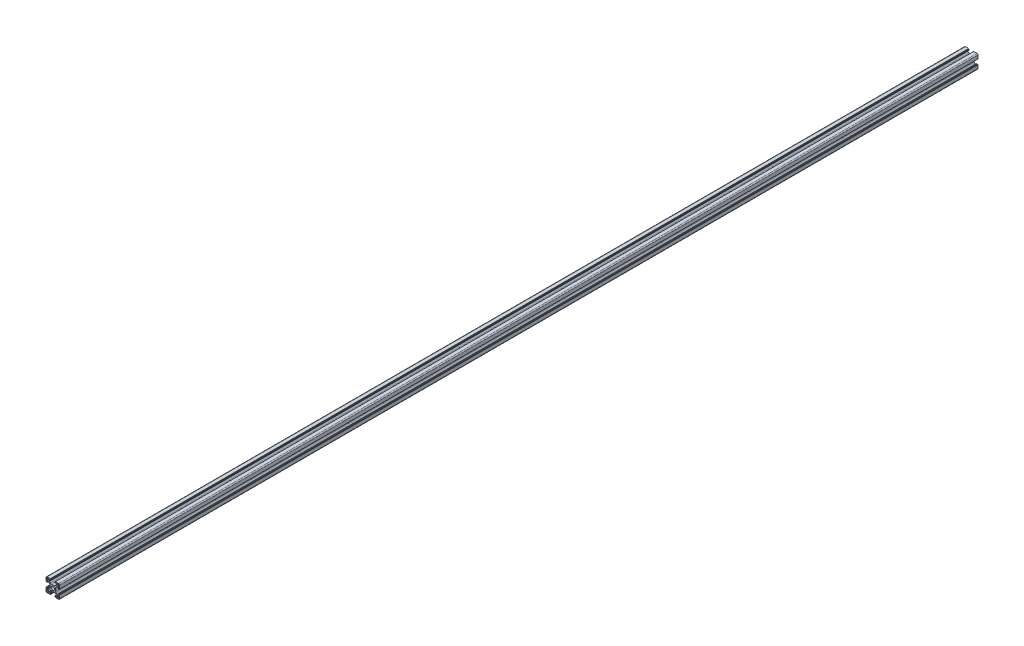
SolidWorks part; units mm, degrees
material "1060 Сплав"
ref_plane "Спереди" through (0, 0, 0) normal (0, 0, 1) x (1, 0, 0)
ref_plane "Сверху" through (0, 0, 0) normal (0, 1, 0) x (1, 0, 0)
ref_plane "Справа" through (0, 0, 0) normal (1, 0, 0) x (0, 0, -1)
sketch "Эскиз1" plane through (0, 0, 0) normal (0, 0, 1) x (1, 0, 0)
  line L0 (9.3595, 9.1357) -> (6.3595, 6.1357) construction
  line L1 (0.2595, 4.0357) -> (2.1582, 4.0357)
  line L2 (0.2595, 0.0357) -> (10.2595, 10.0357) construction
  line L3 (7.8595, 7.6357) -> (6.3595, 9.1357) construction
  line L4 (3.5725, 4.6215) -> (4.8737, 5.9227)
  line L5 (7.1595, 6.1357) -> (8.5595, 6.1357)
  line L6 (6.3595, 6.9357) -> (6.3595, 8.3357)
  line L7 (8.5595, 9.1357) -> (7.1595, 9.1357)
  line L8 (5.4595, 8.2357) -> (5.4595, 7.3369)
  line L9 (4.0227, 8.1089) -> (4.503, 8.5893)
  line L10 (3.4595, 9.5848) -> (3.9595, 9.5848)
  line L11 (3.8459, 8.0357) -> (3.5595, 8.0357)
  line L12 (4.8566, 8.7357) -> (4.9595, 8.7357)
  line L13 (3.9595, 9.8857) -> (3.9595, 9.5848)
  line L14 (3.3095, 9.4348) -> (3.3095, 8.2857)
  line L15 (8.7595, 10.0357) -> (4.1095, 10.0357)
  line L16 (9.3595, 8.3357) -> (9.3595, 6.9357)
  line L17 (10.2595, 8.5357) -> (10.2595, 3.8857)
  line L18 (9.6585, 3.0857) -> (8.5095, 3.0857)
  line L19 (10.1095, 3.7357) -> (9.8085, 3.7357)
  line L20 (8.9595, 4.6328) -> (8.9595, 4.7357)
  line L21 (8.2595, 3.6221) -> (8.2595, 3.3357)
  line L22 (9.8085, 3.2357) -> (9.8085, 3.7357)
  line L23 (8.3327, 3.7989) -> (8.813, 4.2793)
  line L24 (8.4595, 5.2357) -> (7.5607, 5.2357)
  line L25 (4.8452, 3.3487) -> (6.1465, 4.6499)
  line L26 (4.2595, 0.0357) -> (4.2595, 1.9345)
  line L27 (4.2595, 0.0357) -> (4.2595, -1.8631)
  line L28 (4.8452, -3.2773) -> (6.1465, -4.5785)
  line L29 (6.3595, -6.8643) -> (6.3595, -8.2643)
  line L30 (7.1595, -6.0643) -> (8.5595, -6.0643)
  line L31 (9.3595, -8.2643) -> (9.3595, -6.8643)
  line L32 (8.4595, -5.1643) -> (7.5607, -5.1643)
  line L33 (8.3327, -3.7275) -> (8.813, -4.2079)
  line L34 (9.8085, -3.1643) -> (9.8085, -3.6643)
  line L35 (8.2595, -3.5507) -> (8.2595, -3.2643)
  line L36 (8.9595, -4.5614) -> (8.9595, -4.6643)
  line L37 (10.1095, -3.6643) -> (9.8085, -3.6643)
  line L38 (9.6585, -3.0143) -> (8.5095, -3.0143)
  line L39 (10.2595, -8.4643) -> (10.2595, -3.8143)
  line L40 (8.5595, -9.0643) -> (7.1595, -9.0643)
  line L41 (8.7595, -9.9643) -> (4.1095, -9.9643)
  line L42 (3.3095, -9.3634) -> (3.3095, -8.2143)
  line L43 (3.9595, -9.8143) -> (3.9595, -9.5134)
  line L44 (4.8566, -8.6643) -> (4.9595, -8.6643)
  line L45 (3.8459, -7.9643) -> (3.5595, -7.9643)
  line L46 (3.4595, -9.5134) -> (3.9595, -9.5134)
  line L47 (4.0227, -8.0375) -> (4.503, -8.5179)
  line L48 (5.4595, -8.1643) -> (5.4595, -7.2655)
  line L49 (3.5725, -4.5501) -> (4.8737, -5.8513)
  line L50 (0.2595, -3.9643) -> (2.1582, -3.9643)
  line L51 (9.3595, -9.0643) -> (6.3595, -6.0643) construction
  line L52 (0.2595, 0.0357) -> (10.2595, -9.9643) construction
  line L53 (7.8595, -7.5643) -> (9.3595, -6.0643) construction
  line L54 (0.2595, -3.9643) -> (-1.6393, -3.9643)
  line L55 (-3.0535, -4.5501) -> (-4.3548, -5.8513)
  line L56 (-6.6405, -6.0643) -> (-8.0405, -6.0643)
  line L57 (-5.8405, -6.8643) -> (-5.8405, -8.2643)
  line L58 (-8.0405, -9.0643) -> (-6.6405, -9.0643)
  line L59 (-4.9405, -8.1643) -> (-4.9405, -7.2655)
  line L60 (-3.5038, -8.0375) -> (-3.9841, -8.5179)
  line L61 (-2.9405, -9.5134) -> (-3.4405, -9.5134)
  line L62 (-3.327, -7.9643) -> (-3.0405, -7.9643)
  line L63 (-4.3376, -8.6643) -> (-4.4405, -8.6643)
  line L64 (-3.4405, -9.8143) -> (-3.4405, -9.5134)
  line L65 (-2.7905, -9.3634) -> (-2.7905, -8.2143)
  line L66 (-8.2405, -9.9643) -> (-3.5905, -9.9643)
  line L67 (-8.8405, -8.2643) -> (-8.8405, -6.8643)
  line L68 (-9.7405, -8.4643) -> (-9.7405, -3.8143)
  line L69 (-9.1396, -3.0143) -> (-7.9905, -3.0143)
  line L70 (-9.5905, -3.6643) -> (-9.2896, -3.6643)
  line L71 (-8.4405, -4.5614) -> (-8.4405, -4.6643)
  line L72 (-7.7405, -3.5507) -> (-7.7405, -3.2643)
  line L73 (-9.2896, -3.1643) -> (-9.2896, -3.6643)
  line L74 (-7.8138, -3.7275) -> (-8.2941, -4.2079)
  line L75 (-7.9405, -5.1643) -> (-7.0418, -5.1643)
  line L76 (-4.3263, -3.2773) -> (-5.6275, -4.5785)
  line L77 (-3.7405, 0.0357) -> (-3.7405, -1.8631)
  line L78 (-8.8405, -9.0643) -> (-5.8405, -6.0643) construction
  line L79 (0.2595, 0.0357) -> (-9.7405, -9.9643) construction
  line L80 (-7.3405, -7.5643) -> (-5.8405, -9.0643) construction
  line L81 (-3.7405, 0.0357) -> (-3.7405, 1.9345)
  line L82 (-4.3263, 3.3487) -> (-5.6275, 4.6499)
  line L83 (-5.8405, 6.9357) -> (-5.8405, 8.3357)
  line L84 (-6.6405, 6.1357) -> (-8.0405, 6.1357)
  line L85 (-8.8405, 8.3357) -> (-8.8405, 6.9357)
  line L86 (-7.9405, 5.2357) -> (-7.0418, 5.2357)
  line L87 (-7.8138, 3.7989) -> (-8.2941, 4.2793)
  line L88 (-9.2896, 3.2357) -> (-9.2896, 3.7357)
  line L89 (-7.7405, 3.6221) -> (-7.7405, 3.3357)
  line L90 (-8.4405, 4.6328) -> (-8.4405, 4.7357)
  line L91 (-9.5905, 3.7357) -> (-9.2896, 3.7357)
  line L92 (-9.1396, 3.0857) -> (-7.9905, 3.0857)
  line L93 (-9.7405, 8.5357) -> (-9.7405, 3.8857)
  line L94 (-8.0405, 9.1357) -> (-6.6405, 9.1357)
  line L95 (-8.2405, 10.0357) -> (-3.5905, 10.0357)
  line L96 (-2.7905, 9.4348) -> (-2.7905, 8.2857)
  line L97 (-3.4405, 9.8857) -> (-3.4405, 9.5848)
  line L98 (-4.3376, 8.7357) -> (-4.4405, 8.7357)
  line L99 (-3.327, 8.0357) -> (-3.0405, 8.0357)
  line L100 (-2.9405, 9.5848) -> (-3.4405, 9.5848)
  line L101 (-3.5038, 8.1089) -> (-3.9841, 8.5893)
  line L102 (-4.9405, 8.2357) -> (-4.9405, 7.3369)
  line L103 (-3.0535, 4.6215) -> (-4.3548, 5.9227)
  line L104 (0.2595, 4.0357) -> (-1.6393, 4.0357)
  line L105 (-11.5046, 0.0357) -> (11.7638, 0.0357) construction
  line L106 (-8.8405, 9.1357) -> (-5.8405, 6.1357) construction
  line L107 (0.2595, -12.0507) -> (0.2595, 10.7546) construction
  line L108 (0.2595, 0.0357) -> (-9.7405, 10.0357) construction
  line L109 (-7.3405, 7.6357) -> (-8.8405, 6.1357) construction
  arc A0 (9.3595, 8.3357) -> (8.5595, 9.1357) centre (8.5595, 8.3357) ccw
  arc A1 (7.1595, 9.1357) -> (6.3595, 8.3357) centre (7.1595, 8.3357) ccw
  arc A2 (7.1595, 6.1357) -> (6.3595, 6.9357) centre (7.1595, 6.9357) cw
  arc A3 (8.7595, 10.0357) -> (10.2595, 8.5357) centre (8.7595, 8.5357) cw
  arc A4 (3.4595, 9.5848) -> (3.3095, 9.4348) centre (3.4595, 9.4348) ccw
  arc A5 (4.1095, 10.0357) -> (3.9595, 9.8857) centre (4.1095, 9.8857) ccw
  arc A6 (3.8459, 8.0357) -> (4.0227, 8.1089) centre (3.8459, 8.2857) ccw
  arc A7 (3.5595, 8.0357) -> (3.3095, 8.2857) centre (3.5595, 8.2857) cw
  arc A8 (4.503, 8.5893) -> (4.8566, 8.7357) centre (4.8566, 8.2357) cw
  arc A9 (4.9595, 8.7357) -> (5.4595, 8.2357) centre (4.9595, 8.2357) cw
  arc A10 (2.7595, 0.0357) -> (0.2595, 2.5357) centre (0.2595, 0.0357) ccw
  arc A11 (2.1582, 4.0357) -> (3.5725, 4.6215) centre (2.1582, 6.0357) ccw
  arc A12 (5.4595, 7.3369) -> (4.8737, 5.9227) centre (3.4595, 7.3369) cw
  arc A13 (9.3595, 6.9357) -> (8.5595, 6.1357) centre (8.5595, 6.9357) cw
  arc A14 (8.9595, 4.7357) -> (8.4595, 5.2357) centre (8.4595, 4.7357) ccw
  arc A15 (8.813, 4.2793) -> (8.9595, 4.6328) centre (8.4595, 4.6328) ccw
  arc A16 (8.2595, 3.3357) -> (8.5095, 3.0857) centre (8.5095, 3.3357) ccw
  arc A17 (8.2595, 3.6221) -> (8.3327, 3.7989) centre (8.5095, 3.6221) cw
  arc A18 (10.2595, 3.8857) -> (10.1095, 3.7357) centre (10.1095, 3.8857) cw
  arc A19 (9.8085, 3.2357) -> (9.6585, 3.0857) centre (9.6585, 3.2357) cw
  arc A20 (7.5607, 5.2357) -> (6.1465, 4.6499) centre (7.5607, 3.2357) ccw
  arc A21 (4.2595, 1.9345) -> (4.8452, 3.3487) centre (6.2595, 1.9345) cw
  arc A22 (8.5595, -9.0643) -> (9.3595, -8.2643) centre (8.5595, -8.2643) ccw
  arc A23 (9.3595, -6.8643) -> (8.5595, -6.0643) centre (8.5595, -6.8643) ccw
  arc A24 (6.3595, -6.8643) -> (7.1595, -6.0643) centre (7.1595, -6.8643) cw
  arc A25 (10.2595, -8.4643) -> (8.7595, -9.9643) centre (8.7595, -8.4643) cw
  arc A26 (9.8085, -3.1643) -> (9.6585, -3.0143) centre (9.6585, -3.1643) ccw
  arc A27 (10.2595, -3.8143) -> (10.1095, -3.6643) centre (10.1095, -3.8143) ccw
  arc A28 (8.2595, -3.5507) -> (8.3327, -3.7275) centre (8.5095, -3.5507) ccw
  arc A29 (8.2595, -3.2643) -> (8.5095, -3.0143) centre (8.5095, -3.2643) cw
  arc A30 (8.813, -4.2079) -> (8.9595, -4.5614) centre (8.4595, -4.5614) cw
  arc A31 (8.9595, -4.6643) -> (8.4595, -5.1643) centre (8.4595, -4.6643) cw
  arc A32 (0.2595, -2.4643) -> (2.7595, 0.0357) centre (0.2595, 0.0357) ccw
  arc A33 (4.2595, -1.8631) -> (4.8452, -3.2773) centre (6.2595, -1.8631) ccw
  arc A34 (7.5607, -5.1643) -> (6.1465, -4.5785) centre (7.5607, -3.1643) cw
  arc A35 (7.1595, -9.0643) -> (6.3595, -8.2643) centre (7.1595, -8.2643) cw
  arc A36 (4.9595, -8.6643) -> (5.4595, -8.1643) centre (4.9595, -8.1643) ccw
  arc A37 (4.503, -8.5179) -> (4.8566, -8.6643) centre (4.8566, -8.1643) ccw
  arc A38 (3.5595, -7.9643) -> (3.3095, -8.2143) centre (3.5595, -8.2143) ccw
  arc A39 (3.8459, -7.9643) -> (4.0227, -8.0375) centre (3.8459, -8.2143) cw
  arc A40 (4.1095, -9.9643) -> (3.9595, -9.8143) centre (4.1095, -9.8143) cw
  arc A41 (3.4595, -9.5134) -> (3.3095, -9.3634) centre (3.4595, -9.3634) cw
  arc A42 (5.4595, -7.2655) -> (4.8737, -5.8513) centre (3.4595, -7.2655) ccw
  arc A43 (2.1582, -3.9643) -> (3.5725, -4.5501) centre (2.1582, -5.9643) cw
  arc A44 (-8.8405, -8.2643) -> (-8.0405, -9.0643) centre (-8.0405, -8.2643) ccw
  arc A45 (-6.6405, -9.0643) -> (-5.8405, -8.2643) centre (-6.6405, -8.2643) ccw
  arc A46 (-6.6405, -6.0643) -> (-5.8405, -6.8643) centre (-6.6405, -6.8643) cw
  arc A47 (-8.2405, -9.9643) -> (-9.7405, -8.4643) centre (-8.2405, -8.4643) cw
  arc A48 (-2.9405, -9.5134) -> (-2.7905, -9.3634) centre (-2.9405, -9.3634) ccw
  arc A49 (-3.5905, -9.9643) -> (-3.4405, -9.8143) centre (-3.5905, -9.8143) ccw
  arc A50 (-3.327, -7.9643) -> (-3.5038, -8.0375) centre (-3.327, -8.2143) ccw
  arc A51 (-3.0405, -7.9643) -> (-2.7905, -8.2143) centre (-3.0405, -8.2143) cw
  arc A52 (-3.9841, -8.5179) -> (-4.3376, -8.6643) centre (-4.3376, -8.1643) cw
  arc A53 (-4.4405, -8.6643) -> (-4.9405, -8.1643) centre (-4.4405, -8.1643) cw
  arc A54 (-2.2405, 0.0357) -> (0.2595, -2.4643) centre (0.2595, 0.0357) ccw
  arc A55 (-1.6393, -3.9643) -> (-3.0535, -4.5501) centre (-1.6393, -5.9643) ccw
  arc A56 (-4.9405, -7.2655) -> (-4.3548, -5.8513) centre (-2.9405, -7.2655) cw
  arc A57 (-8.8405, -6.8643) -> (-8.0405, -6.0643) centre (-8.0405, -6.8643) cw
  arc A58 (-8.4405, -4.6643) -> (-7.9405, -5.1643) centre (-7.9405, -4.6643) ccw
  arc A59 (-8.2941, -4.2079) -> (-8.4405, -4.5614) centre (-7.9405, -4.5614) ccw
  arc A60 (-7.7405, -3.2643) -> (-7.9905, -3.0143) centre (-7.9905, -3.2643) ccw
  arc A61 (-7.7405, -3.5507) -> (-7.8138, -3.7275) centre (-7.9905, -3.5507) cw
  arc A62 (-9.7405, -3.8143) -> (-9.5905, -3.6643) centre (-9.5905, -3.8143) cw
  arc A63 (-9.2896, -3.1643) -> (-9.1396, -3.0143) centre (-9.1396, -3.1643) cw
  arc A64 (-7.0418, -5.1643) -> (-5.6275, -4.5785) centre (-7.0418, -3.1643) ccw
  arc A65 (-3.7405, -1.8631) -> (-4.3263, -3.2773) centre (-5.7405, -1.8631) cw
  arc A66 (-8.0405, 9.1357) -> (-8.8405, 8.3357) centre (-8.0405, 8.3357) ccw
  arc A67 (-8.8405, 6.9357) -> (-8.0405, 6.1357) centre (-8.0405, 6.9357) ccw
  arc A68 (-5.8405, 6.9357) -> (-6.6405, 6.1357) centre (-6.6405, 6.9357) cw
  arc A69 (-9.7405, 8.5357) -> (-8.2405, 10.0357) centre (-8.2405, 8.5357) cw
  arc A70 (-9.2896, 3.2357) -> (-9.1396, 3.0857) centre (-9.1396, 3.2357) ccw
  arc A71 (-9.7405, 3.8857) -> (-9.5905, 3.7357) centre (-9.5905, 3.8857) ccw
  arc A72 (-7.7405, 3.6221) -> (-7.8138, 3.7989) centre (-7.9905, 3.6221) ccw
  arc A73 (-7.7405, 3.3357) -> (-7.9905, 3.0857) centre (-7.9905, 3.3357) cw
  arc A74 (-8.2941, 4.2793) -> (-8.4405, 4.6328) centre (-7.9405, 4.6328) cw
  arc A75 (-8.4405, 4.7357) -> (-7.9405, 5.2357) centre (-7.9405, 4.7357) cw
  arc A76 (0.2595, 2.5357) -> (-2.2405, 0.0357) centre (0.2595, 0.0357) ccw
  arc A77 (-3.7405, 1.9345) -> (-4.3263, 3.3487) centre (-5.7405, 1.9345) ccw
  arc A78 (-7.0418, 5.2357) -> (-5.6275, 4.6499) centre (-7.0418, 3.2357) cw
  arc A79 (-6.6405, 9.1357) -> (-5.8405, 8.3357) centre (-6.6405, 8.3357) cw
  arc A80 (-4.4405, 8.7357) -> (-4.9405, 8.2357) centre (-4.4405, 8.2357) ccw
  arc A81 (-3.9841, 8.5893) -> (-4.3376, 8.7357) centre (-4.3376, 8.2357) ccw
  arc A82 (-3.0405, 8.0357) -> (-2.7905, 8.2857) centre (-3.0405, 8.2857) ccw
  arc A83 (-3.327, 8.0357) -> (-3.5038, 8.1089) centre (-3.327, 8.2857) cw
  arc A84 (-3.5905, 10.0357) -> (-3.4405, 9.8857) centre (-3.5905, 9.8857) cw
  arc A85 (-2.9405, 9.5848) -> (-2.7905, 9.4348) centre (-2.9405, 9.4348) cw
  arc A86 (-4.9405, 7.3369) -> (-4.3548, 5.9227) centre (-2.9405, 7.3369) ccw
  arc A87 (-1.6393, 4.0357) -> (-3.0535, 4.6215) centre (-1.6393, 6.0357) cw
  point P0 (0.2595, 0.0357)
  point P9 (0.2595, 0.0357)
  point P40 (8.9595, 3.7357)
  point P93 (3.9595, -8.6643)
  point P144 (3.9595, 8.7357)
  point P152 (8.9595, -3.6643)
  point P153 (0.2595, -3.8886)
  point P154 (0.2595, 0.0357)
  point P189 (-8.4405, -3.6643)
  point P228 (-3.4405, -8.6643)
  point P229 (-3.6648, 0.0357)
  point P230 (0.2595, 0.0357)
  point P268 (-3.4405, 8.7357)
  point P273 (4.1837, 0.0357)
  point P306 (-8.4405, 3.7357)
  point P307 (0.2595, 3.96)
  point P309 (0.2595, 0.0357)
  dimension "D3" = 5
  dimension "D6" = 2
  dimension "D1" = 2
  dimension "D2" = 6
  dimension "D4" = 4
  dimension "D5" = 0.9
extrude "Бобышка-Вытянуть1" add sketch "Эскиз1" along normal blind 1350
